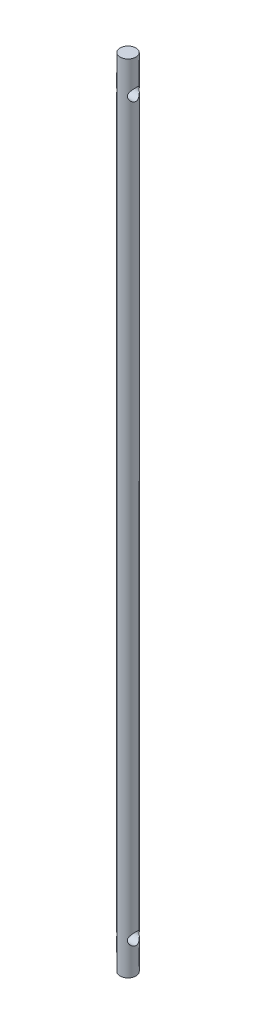
SolidWorks part; units mm, degrees
material "AISI 类型 A2 刀具钢"
ref_plane "前视基准面" through (0, 0, 0) normal (0, 0, 1) x (1, 0, 0)
ref_plane "上视基准面" through (0, 0, 0) normal (0, 1, 0) x (1, 0, 0)
ref_plane "右视基准面" through (0, 0, 0) normal (1, 0, 0) x (0, 0, -1)
sketch "草图1" plane through (0, 0, 0) normal (0, 1, 0) x (1, 0, 0)
  circle A0 centre (0, 0) radius 2
extrude "凸台-拉伸1" add sketch "草图1" along normal blind 200
sketch "草图2" plane through (0, 0, 0) normal (1, 0, 0) x (0, 0, -1)
  line L0 (11.835, 100) -> (-10.8664, 100) construction
  circle A0 centre (0, 8.1472) radius 1.5
  circle A1 centre (0, 191.8528) radius 1.5
extrude "切除-拉伸3" cut sketch "草图2" against normal mid plane 200
